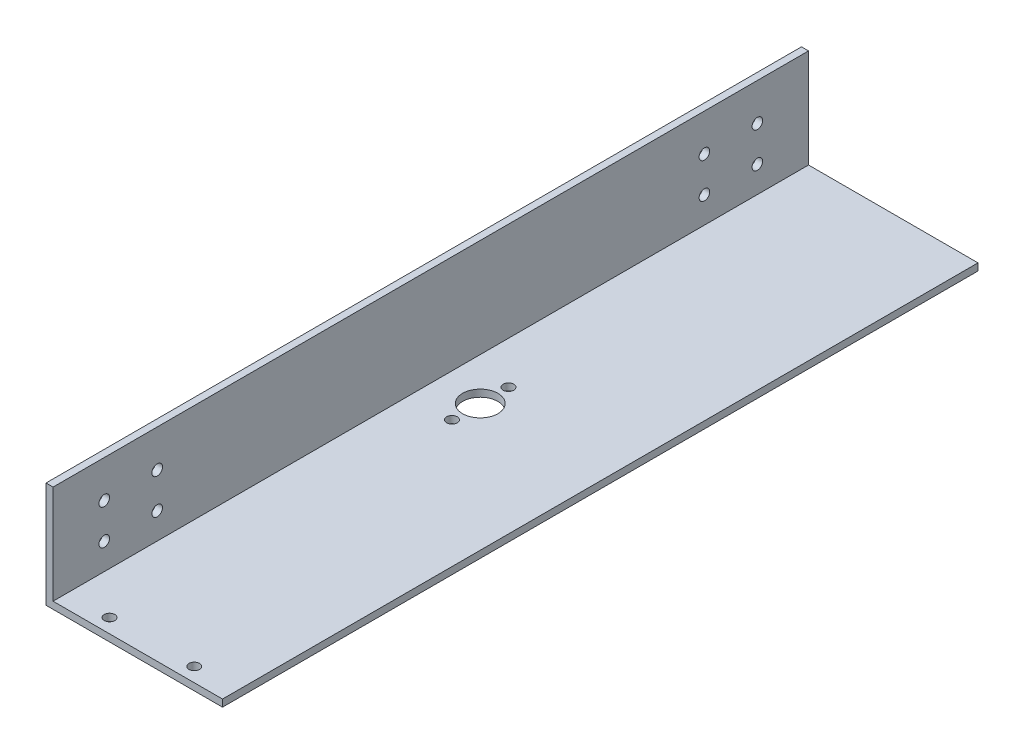
SolidWorks part; units mm, degrees
ref_plane "Front Plane" through (0, 0, 0) normal (0, 0, 1) x (1, 0, 0)
ref_plane "Top Plane" through (0, 0, 0) normal (0, 1, 0) x (1, 0, 0)
ref_plane "Right Plane" through (0, 0, 0) normal (1, 0, 0) x (0, 0, -1)
sketch "Sketch1" plane through (0, 0, 0) normal (0, 0, 1) x (1, 0, 0)
  line L0 (0, 0) -> (0, 30)
  line L1 (0, 30) -> (2, 30)
  line L2 (2, 30) -> (2, 2)
  line L3 (2, 2) -> (50, 2)
  line L4 (50, 2) -> (50, 0)
  line L5 (50, 0) -> (0, 0)
extrude "Boss-Extrude1" add sketch "Sketch1" along normal up to surface (214 mm away)
sketch "Sketch2" plane through (0, 0, 0) normal (0, -1, 0) x (1, 0, 0)
  circle A0 centre (14, 105) radius 5
extrude "Cut-Extrude1" cut sketch "Sketch2" against normal through all
sketch "Sketch4" plane through (0, 0, 0) normal (0, -1, 0) x (-1, 0, 0)
  circle A0 centre (-14, -113) radius 1.5
  circle A1 centre (-14, -97) radius 1.5
extrude "Cut-Extrude3" cut sketch "Sketch4" against normal through all
sketch "Sketch6" plane through (2, 0, 0) normal (1, 0, 0) x (0, 0, -1)
  circle A0 centre (-199.5, 9.45) radius 1.5
  circle A1 centre (-199.5, 19.45) radius 1.5
  circle A2 centre (-184.5, 9.45) radius 1.5
  circle A3 centre (-184.5, 19.45) radius 1.5
hole_wizard "Ø3.0 (3) Diameter Hole1" positions "Sketch7" profile "Sketch8" hole size "Ø3.0" standard "ISO" end condition through all
sketch "Sketch7" plane through (2, 0, 0) normal (1, 0, 0) x (0, 0, -1)
  point P0 (-199.5, 9.45)
  point P3 (-199.5, 19.45)
  point P6 (-184.5, 19.45)
  point P9 (-184.5, 9.45)
  point P12 (-29.5, 19.45)
  point P15 (-29.5, 9.45)
  point P18 (-14.5, 9.45)
  point P21 (-14.5, 19.45)
sketch "Sketch8" plane through (2, 9.45, 199.5) normal (0, 1, 0) x (0, 0, -1)
  line L0 (0, 0) -> (0, 2)
  line L1 (0, 2) -> (1.5, 2)
  line L2 (1.5, 2) -> (1.5, 0)
  line L5 (1.5, 0) -> (0, 0)
  line L11 (0, -6.35) -> (0, 107.95) construction
  dimension "Thru Hole Dia." = 3
  dimension "Thru Hole Depth" = 2
hole_wizard "Ø3.0 (3) Diameter Hole2" positions "Sketch11" profile "Sketch12" hole size "Ø3.0" standard "ISO" end condition through all
sketch "Sketch11" plane through (-23.4076, 2, 151.138) normal (0, 1, 0) x (0, 0, 1)
  point P0 (58.862, 61.4076)
  point P1 (58.862, 37.4076)
sketch "Sketch12" plane through (38, 2, 210) normal (1, 0, 0) x (0, 0, 1)
  line L0 (0, 0) -> (0, 2)
  line L1 (0, 2) -> (1.5, 2)
  line L2 (1.5, 2) -> (1.5, 0)
  line L3 (1.5, 0) -> (0, 0)
  line L4 (0, 110) -> (0, -10) construction
  dimension "Diameter" = 3
  dimension "Depth" = 2
